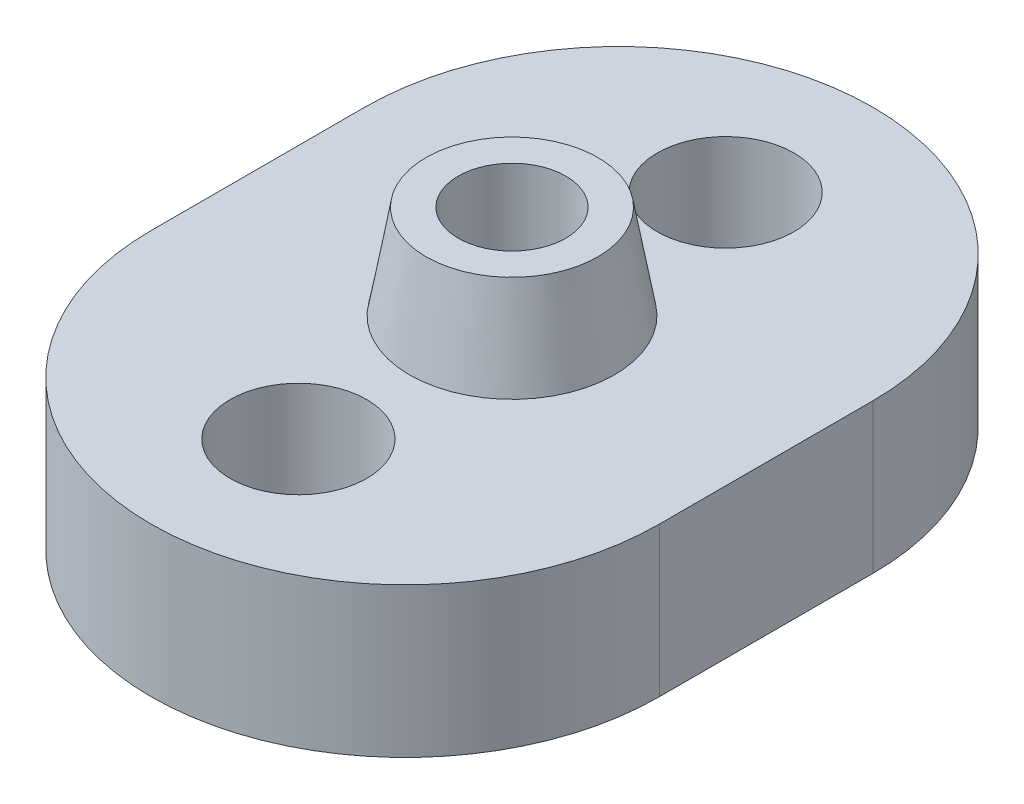
SolidWorks part; units mm, degrees
material "Glass"
ref_plane "Front Plane" through (0, 0, 0) normal (0, 0, 1) x (1, 0, 0)
ref_plane "Top Plane" through (0, 0, 0) normal (0, 1, 0) x (1, 0, 0)
ref_plane "Right Plane" through (0, 0, 0) normal (1, 0, 0) x (0, 0, -1)
sketch "Sketch1" plane through (0, 0, 0) normal (0, 1, 0) x (1, 0, 0)
  line L0 (-3.45, 0) -> (3.45, 0) construction
  line L1 (-3.45, 2.4) -> (3.45, 2.4) construction
  line L2 (-3.45, -2.4) -> (3.45, -2.4) construction
  arc A0 (-3.45, 2.4) -> (-3.45, -2.4) centre (-3.45, 0) ccw construction
  arc A1 (3.45, -2.4) -> (3.45, 2.4) centre (3.45, 0) ccw construction
  circle A2 centre (0, 0) radius 2.4
  point P2 (0, 0)
extrude "Boss-Extrude1" add sketch "Sketch1" along normal blind 2.2 draft 10
sketch "Sketch2" plane through (0, 0, 0) normal (0, -1, 0) x (1, 0, 0)
  line L0 (0, -2.5) -> (0, 2.5) construction
  line L1 (-5.95, -2.5) -> (-5.95, 2.5)
  line L2 (5.95, -2.5) -> (5.95, 2.5)
  arc A0 (-5.95, -2.5) -> (5.95, -2.5) centre (0, -2.5) ccw
  arc A1 (5.95, 2.5) -> (-5.95, 2.5) centre (0, 2.5) ccw
  circle A4 centre (0, -5) radius 1.6
  circle A5 centre (0, 5) radius 1.6
  point P2 (0, 0)
extrude "Boss-Extrude2" add sketch "Sketch2" along normal blind 3.5
sketch "Sketch4" plane through (0, -3.5, 0) normal (0, -1, 0) x (1, 0, 0)
  circle A0 centre (0, 0) radius 1.26
extrude "Cut-Extrude1" cut sketch "Sketch4" against normal through all both and the other way through all
